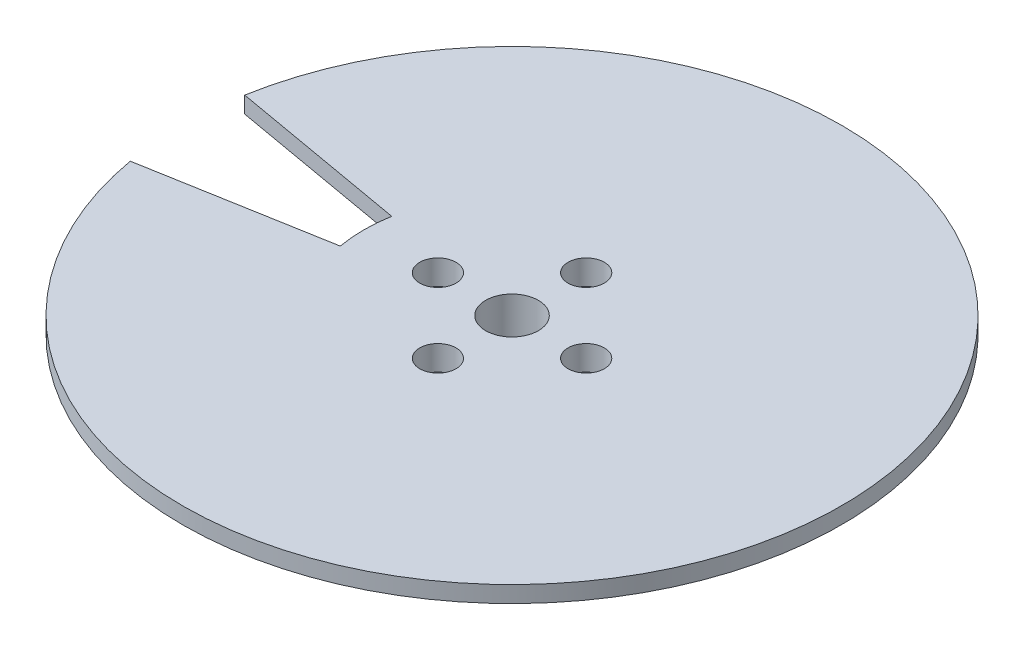
SolidWorks part; units mm, degrees
ref_plane "Front Plane" through (0, 0, 0) normal (0, 0, 1) x (1, 0, 0)
ref_plane "Top Plane" through (0, 0, 0) normal (0, 1, 0) x (1, 0, 0)
ref_plane "Right Plane" through (0, 0, 0) normal (1, 0, 0) x (0, 0, -1)
other "Configuration Table"
sketch "草图1" plane through (0, 0, 0) normal (0, 1, 0) x (1, 0, 0)
  circle A0 centre (0, 0) radius 7.5
  circle A1 centre (0, 0) radius 9
extrude "凸台-拉伸1" add sketch "草图1" along normal blind 6
sketch "草图2" plane through (0, 6, 0) normal (0, 1, 0) x (1, 0, 0)
  line L0 (0, 0) -> (-20, 0) construction
  line L1 (0, 0) -> (-19.6962, 3.473)
  line L2 (0, 0) -> (-19.6962, -3.473)
  circle A0 centre (0, 0) radius 20
  circle A2 centre (0, 0) radius 9
  dimension "D1" = 10
  dimension "D2" = 10
extrude "凸台-拉伸2" add sketch "草图2" against normal blind 1
sketch "草图4" plane through (0, 0, 0) normal (0, -1, 0) x (1, 0, 0)
  line L0 (0.9566, 6.3261) -> (0.8566, 6.3261) construction
  line L1 (0.9496, 7.3388) -> (0.9635, 5.3133) construction
  line L2 (-1.0434, 6.3123) -> (-0.9434, 6.3123) construction
  line L3 (-1.0364, 5.2996) -> (-1.0504, 7.3251) construction
  line L4 (0.8566, 6.3261) -> (0.8566, 7.4509)
  line L5 (0.8566, 6.3261) -> (0.8566, 5.4329)
  line L6 (-0.9434, 6.3123) -> (-0.9434, 7.4404)
  line L7 (-0.9434, 6.3123) -> (-0.9434, 5.4185)
  line L8 (6.3123, 0.9434) -> (5.4185, 0.9434)
  line L9 (6.3123, 0.9434) -> (7.4404, 0.9434)
  line L10 (6.3261, -0.8566) -> (7.4509, -0.8566)
  line L11 (6.3261, -0.8566) -> (5.4329, -0.8566)
  line L12 (0.9434, -6.3123) -> (0.9434, -5.4185)
  line L13 (0.9434, -6.3123) -> (0.9434, -7.4404)
  line L14 (-0.8566, -6.3261) -> (-0.8566, -7.4509)
  line L15 (-0.8566, -6.3261) -> (-0.8566, -5.4329)
  line L16 (-6.3123, -0.9434) -> (-5.4185, -0.9434)
  line L17 (-6.3123, -0.9434) -> (-7.4404, -0.9434)
  line L18 (-6.3261, 0.8566) -> (-7.4509, 0.8566)
  line L19 (-6.3261, 0.8566) -> (-5.4329, 0.8566)
  arc A0 (0.8566, 7.4509) -> (-0.9434, 7.4404) centre (0, 0) ccw
  arc A1 (0.8566, 5.4329) -> (-0.9434, 5.4185) centre (0, 0) ccw
  arc A2 (5.4329, -0.8566) -> (5.4185, 0.9434) centre (0, 0) ccw
  arc A3 (7.4509, -0.8566) -> (7.4404, 0.9434) centre (0, 0) ccw
  arc A4 (-0.8566, -5.4329) -> (0.9434, -5.4185) centre (0, 0) ccw
  arc A5 (-0.8566, -7.4509) -> (0.9434, -7.4404) centre (0, 0) ccw
  arc A6 (-5.4329, 0.8566) -> (-5.4185, -0.9434) centre (0, 0) ccw
  arc A7 (-7.4509, 0.8566) -> (-7.4404, -0.9434) centre (0, 0) ccw
  point P35 (0, 0)
  dimension "D1" = 4
extrude "凸台-拉伸3" add sketch "草图4" against normal blind 3
sketch "草图5" plane through (0, 6, 0) normal (0, 1, 0) x (1, 0, 0)
  circle A0 centre (0, 0) radius 7.5
extrude "凸台-拉伸4" add sketch "草图5" against normal blind 3
sketch "草图6" plane through (0, 6, 0) normal (0, 1, 0) x (1, 0, 0)
  circle A0 centre (0, 0) radius 1.6
extrude "切除-拉伸1" cut sketch "草图6" against normal blind 3
chamfer "倒角1" distance 1 angle 45 1 edges at (0, 0, 9)
sketch "草图14" plane through (0, 6, 0) normal (0, 1, 0) x (1, 0, 0)
  line L0 (0, 0) -> (0, 4.5) construction
  line L1 (0, 0) -> (4.5, 0) construction
  line L2 (0, 0) -> (0, -4.5) construction
  line L3 (0, 0) -> (-4.5, 0) construction
  circle A0 centre (0, 4.5) radius 1.1
  circle A1 centre (4.5, 0) radius 1.1
  circle A2 centre (0, -4.5) radius 1.1
  circle A3 centre (-4.5, 0) radius 1.1
  point P13 (0, 0)
  dimension "D1" = 4
extrude "切除-拉伸4" cut sketch "草图14" against normal blind 1.5
